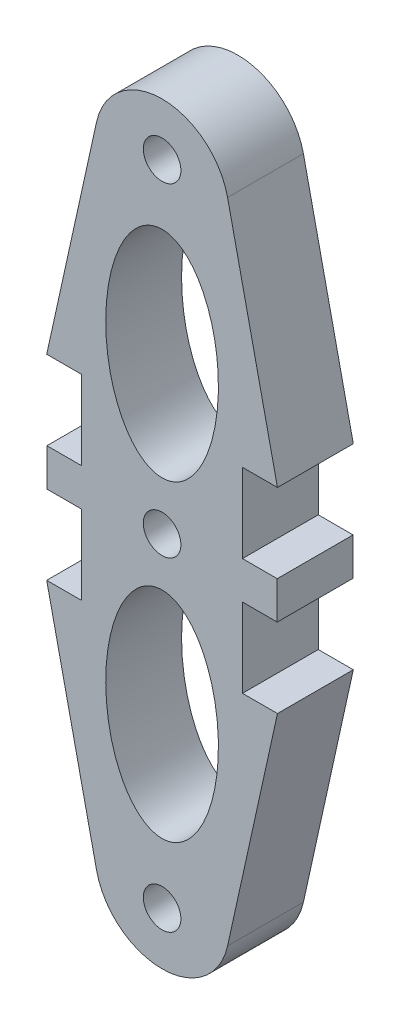
SolidWorks part; units mm, degrees
material "Acrylic (Medium-high impact)"
ref_plane "Front Plane" through (0, 0, 0) normal (0, 0, 1) x (1, 0, 0)
ref_plane "Top Plane" through (0, 0, 0) normal (0, 1, 0) x (1, 0, 0)
ref_plane "Right Plane" through (0, 0, 0) normal (1, 0, 0) x (0, 0, -1)
sketch "Sketch1" plane through (0, 0, 0) normal (0, 0, 1) x (1, 0, 0)
  line L0 (-213.0408, 464.8524) -> (49786.9592, 464.8524) construction
  line L1 (781.4592, 464.8524) -> (778.7761, 464.8524)
  line L2 (781.4592, 464.8524) -> (781.4592, 470.9524)
  line L3 (781.4592, 470.9524) -> (778.7592, 470.9524)
  line L4 (787.6592, -515.9255) -> (787.6592, 49484.0745) construction
  line L5 (-215.2208, 463.4024) -> (49784.7792, 463.4024) construction
  line L6 (793.8592, 470.9524) -> (793.8592, 488.4024) construction
  line L7 (-217.5077, 461.5941) -> (49782.4923, 461.5941) construction
  line L8 (786.2092, -537.0976) -> (786.2092, 49462.9024) construction
  line L9 (789.1092, -536.5976) -> (789.1092, 49463.4024) construction
  line L10 (793.8592, 464.8524) -> (796.5422, 464.8524)
  line L11 (781.4592, 470.9524) -> (793.8592, 470.9524) construction
  line L12 (793.8592, 470.9524) -> (796.5592, 470.9524)
  line L13 (793.8592, 464.8524) -> (793.8592, 470.9524)
  line L14 (778.7761, 464.8524) -> (778.7761, 461.9524)
  line L15 (796.5422, 464.8524) -> (796.5422, 461.9524)
  line L16 (786.2092, 488.4024) -> (782.6065, 488.4024) construction
  line L17 (781.4592, 461.9524) -> (778.7761, 461.9524)
  line L18 (793.8592, 470.9524) -> (793.1379, 470.9192) construction
  line L19 (781.4592, 455.8524) -> (778.7592, 455.8524)
  line L20 (781.4592, 461.9524) -> (781.4592, 455.8524)
  line L21 (793.8592, 461.9524) -> (796.5422, 461.9524)
  line L22 (793.8592, 461.9524) -> (793.8592, 455.8524)
  line L23 (793.8592, 455.8524) -> (796.5592, 455.8524)
  line L24 (778.7592, 470.9524) -> (782.6065, 488.4024)
  line L25 (792.7118, 488.4024) -> (796.5592, 470.9524)
  line L26 (792.7118, 438.4024) -> (796.5592, 455.8524)
  line L27 (789.1092, 438.4024) -> (792.7118, 438.4024) construction
  line L28 (786.2092, 438.4024) -> (782.6065, 438.4024) construction
  line L29 (778.7592, 455.8524) -> (782.6065, 438.4024)
  line L35 (789.1092, 488.4024) -> (792.7118, 488.4024) construction
  arc A0 (782.6065, 488.4024) -> (792.7118, 488.4024) centre (787.6592, 487.2884) cw
  arc A1 (782.6065, 438.4024) -> (792.7118, 438.4024) centre (787.6592, 439.5164) ccw
  circle A3 centre (787.6592, 488.4024) radius 1.45
  circle A5 centre (787.6592, 438.4024) radius 1.45
  circle A6 centre (787.6592, 463.4024) radius 1.45
  ellipse E0 centre (787.6592, 475.4481) end of major axis (787.6592, 483.7502) minor radius 4.3465
  ellipse E1 centre (787.6592, 451.3566) end of major axis (787.6592, 443.0545) minor radius 4.3465
  point P10 (786.4306, 463.4024)
  point P19 (782.4923, 461.5941)
  point P22 (780.2592, 463.4024)
  dimension "D1" = 2.9
  dimension "D3" = 6.1
  dimension "D2" = 2.7
  dimension "D4" = 25
  dimension "D5" = 12.4
extrude "Boss-Extrude1" add sketch "Sketch1" along normal blind 5.85
